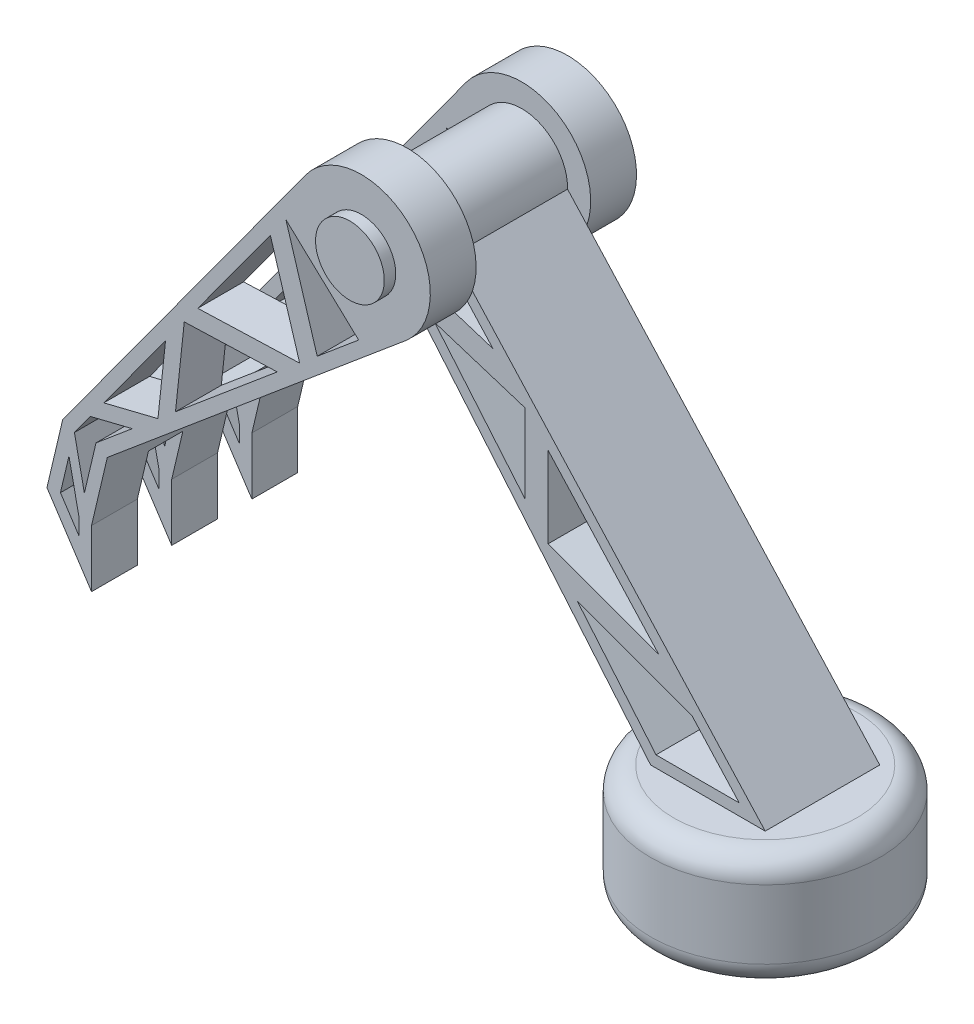
SolidWorks part; units mm, degrees
ref_plane "Front Plane" through (0, 0, 0) normal (0, 0, 1) x (1, 0, 0)
ref_plane "Top Plane" through (0, 0, 0) normal (0, 1, 0) x (1, 0, 0)
ref_plane "Right Plane" through (0, 0, 0) normal (1, 0, 0) x (0, 0, -1)
sketch "Sketch2" plane through (0, 0, 0) normal (0, 1, 0) x (1, 0, 0)
  circle A0 centre (0, 0) radius 12.7
  dimension "D1" = 25.4
extrude "Boss-Extrude1" add sketch "Sketch2" along normal blind 12.7
sketch "Sketch3" plane through (0, 0, 0) normal (0, 0, 1) x (1, 0, 0)
  line L0 (6.35, 12.7) -> (-28.263, 50.6802)
  line L1 (12.7, 12.7) -> (-12.7, 12.7) construction
  line L2 (-6.35, 12.7) -> (-34.1055, 45.7778)
  line L3 (0, 0) -> (0, 23.1747) construction
  line L4 (-12.7, 0) -> (12.7, 0) construction
  line L5 (-34.1055, 45.7778) -> (-28.263, 50.6802) construction
  line L6 (-6.35, 12.7) -> (6.35, 12.7)
  arc A0 (-28.263, 50.6802) -> (-34.1055, 45.7778) centre (-33.3416, 50.8) ccw
  dimension "D5" = 10.16
  dimension "D1" = 6.35
  dimension "D2" = 6.35
  dimension "D3" = 177.656
  dimension "D4" = 7.6269
  dimension "D6" = 50
  dimension "D8" = 50.8
extrude "Boss-Extrude2" add sketch "Sketch3" along normal mid plane 12.7 contours L0 A0 L2 L6
sketch "Sketch4" plane through (0, 0, 6.35) normal (0, 0, 1) x (1, 0, 0)
  line L6 (-5.7578, 13.97) -> (3.4743, 13.97)
  line L7 (3.4743, 13.97) -> (-29.574, 50.2333)
  line L8 (-33.4666, 46.9921) -> (-5.7578, 13.97)
  line L9 (-5.7578, 13.97) -> (3.4743, 13.97)
  line L10 (3.4743, 13.97) -> (-29.574, 50.2333)
  line L11 (-33.4666, 46.9921) -> (-5.7578, 13.97)
  arc A2 (-29.574, 50.2333) -> (-33.4666, 46.9921) centre (-33.3416, 50.8) ccw
  arc A3 (-29.574, 50.2333) -> (-33.4666, 46.9921) centre (-33.3416, 50.8) ccw
  dimension "D1" = 1.27
extrude "Cut-Extrude1" cut sketch "Sketch4" against normal mid plane 15.24 from surface at -6.35 starting at plane "Front Plane"
sketch "Sketch5" plane through (0, 0, 0) normal (0, 0, 1) x (1, 0, 0)
  line L0 (-33.4666, 46.9921) -> (-23.8227, 43.9225)
  line L1 (3.4743, 13.97) -> (-29.574, 50.2333) construction
  line L2 (-30.2987, 43.2168) -> (-20.2707, 40.0249)
  line L3 (-33.4666, 46.9921) -> (-5.7578, 13.97) construction
  line L4 (-20.2707, 40.0249) -> (-20.2707, 31.2658)
  line L5 (-17.7307, 37.2378) -> (-17.7307, 28.2387)
  line L6 (-17.7307, 28.2387) -> (-5.4588, 23.7721)
  line L7 (-14.4653, 24.3472) -> (-1.7727, 19.7275)
  line L8 (-33.4666, 46.9921) -> (-30.2987, 43.2168)
  line L9 (-23.8227, 43.9225) -> (-20.2707, 40.0249)
  line L10 (-20.2707, 40.0249) -> (-17.7307, 37.2378)
  line L11 (-20.2707, 31.2658) -> (-17.7307, 28.2387)
  line L12 (-20.2707, 40.0249) -> (-17.7307, 37.2378)
  line L13 (-20.2707, 31.2658) -> (-17.7307, 28.2387)
  line L14 (-17.7307, 28.2387) -> (-14.4653, 24.3472)
  line L15 (-5.4588, 23.7721) -> (-1.7727, 19.7275)
  dimension "D1" = 2.6367
  dimension "D2" = 2.54
  dimension "D3" = 2.54
  dimension "D4" = 30
  dimension "D5" = 30
extrude "Boss-Extrude3" add sketch "Sketch5" along normal mid plane 12.7 contours L9 L0 L8 L2 | L4 L11 L5 L10 | L15 L6 L14 L7
sketch "Sketch6" plane through (0, 0, 0) normal (0, 0, 1) x (1, 0, 0)
  circle A0 centre (-33.3416, 50.8) radius 3.81
extrude "Boss-Extrude4" add sketch "Sketch6" along normal mid plane 25.4 contours A0
sketch "Sketch7" plane through (0, 0, 12.7) normal (0, 0, 1) x (1, 0, 0)
  line L0 (-39.5174, 55.3023) -> (-66.4507, 18.3575)
  line L1 (-28.4289, 44.9453) -> (-61.5067, 17.1897)
  line L2 (-68.2023, 10.9415) -> (-63.2583, 3.4238)
  line L7 (-66.4507, 18.3575) -> (-61.5067, 17.1897)
  line L8 (-66.4507, 18.3575) -> (-68.2023, 10.9415)
  line L9 (-68.2023, 10.9415) -> (-63.2583, 9.7738)
  line L10 (-61.5067, 17.1897) -> (-63.2583, 9.7738)
  line L11 (-63.2583, 3.4238) -> (-63.2583, 9.7738)
  line L13 (-6.35, 12.7) -> (-34.1055, 45.7778) construction
  circle A0 centre (-33.3416, 50.8) radius 7.6427
  point P6 (-68.7133, -4.0538)
  point P7 (-59.1925, -2.9318)
  point P12 (-59.2512, -3.4222)
  point P13 (-69.1205, 11.2195)
  point P14 (0, 0)
  point P15 (-70.9529, 3.5497)
  point P16 (-65.6187, -4.1352)
  point P17 (-65.1301, 8.8135)
  point P18 (-66.4075, 18.2464)
  point P19 (-61.3266, 12.8735)
  point P20 (-68.7435, 5.8654)
  point P21 (-72.4812, 9.3695)
  point P22 (-67.7507, 15.7352)
  point P23 (-63.1954, 11.7055)
  point P24 (0, 0)
  point P25 (-65.2194, 1.1447)
  point P26 (-63.5309, 1.3428)
  point P27 (-63.3678, 3.5039)
  point P28 (-66.044, 5.6079)
  point P29 (-63.0524, 3.2744)
  circle M15 centre (-33.3416, 50.8) radius 3.81
  dimension "D1" = 15.2855
  dimension "D2" = 6.35
  dimension "D3" = 5.08
  dimension "D4" = 166.093
  dimension "D5" = 7.62
  dimension "D6" = 45.72
  dimension "D7" = 43.18
  dimension "D8" = 90
extrude "Boss-Extrude5" add sketch "Sketch7" along normal blind 5.08 from surface at -6.35 contours A0 M15 | A0 L0 L7 L1 | L10 L7 L8 L9 | L2 L11 L9 starting at face at (-4.6304, 18.0037, 6.35)
sketch "Sketch10" plane through (0, 0, 11.43) normal (0, 0, 1) x (1, 0, 0)
  line L0 (-65.1559, 17.7622) -> (-64.0514, 12.4934)
  line L1 (-65.7598, 15.2053) -> (-64.6553, 9.9365)
  line L2 (-55.8953, 23.7219) -> (-61.894, 22.2366)
  line L3 (-58.739, 21.3358) -> (-63.3903, 20.1841)
  line L6 (-41.7083, 49.9256) -> (-33.6438, 42.3932)
  line L7 (-33.3416, 50.8) -> (-37.676, 46.1594) construction
  line L8 (-41.7083, 49.9256) -> (-38.2371, 38.539)
  line L9 (-43.4313, 47.5622) -> (-40.1828, 36.9063)
  line L10 (-40.1828, 36.9063) -> (-51.4805, 36.5209)
  line L11 (-42.6691, 34.82) -> (-52.9768, 34.4684)
  line L12 (-64.6553, 9.9365) -> (-62.7598, 17.962)
  line L13 (-62.7598, 17.962) -> (-29.3269, 46.0155)
  line L14 (-38.3886, 54.4793) -> (-65.1559, 17.7622)
  line L15 (-65.1559, 17.7622) -> (-66.7043, 11.2062)
  line L16 (-66.7043, 11.2062) -> (-64.6553, 8.0905)
  line L17 (-64.6553, 8.0905) -> (-64.6553, 9.9365)
  line L18 (-64.6553, 9.9365) -> (-62.7598, 17.962)
  line L19 (-62.7598, 17.962) -> (-29.3269, 46.0155)
  line L20 (-38.3886, 54.4793) -> (-65.1559, 17.7622)
  line L21 (-65.1559, 17.7622) -> (-66.7043, 11.2062)
  line L22 (-66.7043, 11.2062) -> (-64.6553, 8.0905)
  line L23 (-64.6553, 8.0905) -> (-64.6553, 9.9365)
  line L24 (-52.9768, 34.4684) -> (-53.9496, 25.3546)
  line L25 (-55.0521, 31.6216) -> (-55.8953, 23.7219)
  arc A2 (-29.3269, 46.0155) -> (-38.3886, 54.4793) centre (-33.3416, 50.8) ccw
  arc A3 (-29.3269, 46.0155) -> (-38.3886, 54.4793) centre (-33.3416, 50.8) ccw
  point P6 (-37.676, 46.1594)
  point P27 (-62.7598, 21.0787)
  dimension "D2" = 6.35
  dimension "D3" = 2.54
  dimension "D4" = 2.54
  dimension "D5" = 2.54
  dimension "D6" = 30
  dimension "D7" = 30
  dimension "D8" = 75
  dimension "D9" = 2.5569
  dimension "D10" = 2.54
  dimension "D11" = 110
  dimension "D1" = 1.397
extrude "Cut-Extrude2" cut sketch "Sketch10" against normal through all contours L9 L20 L10 | L11 L24 L19 | L25 L20 L2 | L22 L23 L1 L21 | L3 L20 L0 L18 L19 | L8 L19 L6
mirror "Mirror1" about plane through (0, 0, 0) normal (0, 0, 1) of bodies 107
sketch "Sketch14" plane through (0, 0, 0) normal (0, -1, 0) x (1, 0, 0)
  circle A0 centre (0, 0) radius 7.62
  circle A1 centre (0, 0) radius 12.7 construction
  circle A2 centre (0, 0) radius 12.7
  dimension "D1" = 5.08
extrude "Cut-Extrude3" cut sketch "Sketch14" against normal blind 6.35 contours A0
sketch "Sketch15" plane through (0, 0, -6.35) normal (0, 0, 1) x (1, 0, 0)
  line L3 (-66.4507, 18.3575) -> (-61.5067, 17.1897)
  line L8 (-39.5174, 55.3023) -> (-66.4507, 18.3575)
  line L9 (-66.4507, 18.3575) -> (-68.2023, 10.9415)
  line L10 (-68.2023, 10.9415) -> (-63.2583, 3.4238)
  line L11 (-63.2583, 3.4238) -> (-63.2583, 9.7738)
  line L12 (-63.2583, 9.7738) -> (-61.5067, 17.1897)
  line L13 (-61.5067, 17.1897) -> (-31.3502, 42.4941)
  line L14 (-31.3502, 42.4941) -> (-34.1055, 45.7778)
  line L15 (-28.263, 50.6802) -> (-26.1123, 48.3203)
  line L17 (-66.4507, 18.3575) -> (-68.2023, 10.9415)
  line L18 (-68.2023, 10.9415) -> (-63.2583, 3.4238)
  line L19 (-63.2583, 3.4238) -> (-63.2583, 9.7738)
  line L20 (-63.2583, 9.7738) -> (-61.5067, 17.1897)
  arc A2 (-26.1123, 48.3203) -> (-39.5174, 55.3023) centre (-33.3416, 50.8) ccw
  arc A3 (-28.263, 50.6802) -> (-34.1055, 45.7778) centre (-33.3416, 50.8) ccw
  line M17 (-66.7043, 11.2062) -> (-65.7598, 15.2053)
  line M18 (-65.7598, 15.2053) -> (-64.6553, 9.9365)
  line M19 (-64.6553, 9.9365) -> (-64.6553, 8.0905)
  line M20 (-64.6553, 8.0905) -> (-66.7043, 11.2062)
  line M22 (-62.7598, 17.962) -> (-64.0514, 12.4934)
  line M23 (-64.0514, 12.4934) -> (-65.1559, 17.7622)
  line M24 (-65.1559, 17.7622) -> (-63.3903, 20.1841)
  line M31 (-66.4507, 18.3575) -> (-68.2023, 10.9415)
  line M32 (-68.2023, 10.9415) -> (-63.2583, 3.4238)
  line M33 (-63.2583, 3.4238) -> (-63.2583, 9.7738)
  line M34 (-63.2583, 9.7738) -> (-61.5067, 17.1897)
  dimension "D1" = 0
extrude "Boss-Extrude12" add sketch "Sketch15" along normal up to next contours L3 M31 M32 M33 M34 M22 M23 M24 M20 M17 M18 M19
fillet "Fillet1" radius 2.54 2 edges at (0, 0, 12.7) (0, 12.7, 12.7)
sketch "Sketch16" plane through (-42.5878, -28.0075, 0) normal (-0.8355, -0.5495, 0) x (0, 0, 1)
  line L0 (11.43, 46.6168) -> (-11.43, 46.6168) construction
  line L1 (-6.35, 46.6168) -> (6.35, 46.6168)
  line L2 (-6.35, 46.6168) -> (-6.35, 37.6191)
  line L3 (-6.35, 37.6191) -> (6.35, 37.6191)
  line L4 (6.35, 46.6168) -> (6.35, 37.6191)
  line L5 (11.43, 37.6191) -> (-11.43, 37.6191) construction
  line L6 (-11.43, 46.6168) -> (-11.43, 37.6191) construction
  line L7 (11.43, 46.6168) -> (11.43, 37.6191) construction
  line L9 (0, 46.6168) -> (0, 37.6191) construction
  line L10 (-2.54, 46.6168) -> (2.54, 46.6168)
  line L11 (-2.54, 46.6168) -> (-2.54, 37.6191)
  line L12 (-2.54, 37.6191) -> (2.54, 37.6191)
  line L13 (2.54, 46.6168) -> (2.54, 37.6191)
  point P19 (3.3521, 45.644)
  point P20 (0, 46.6168)
  point P21 (0, 46.6168)
  point P22 (2.54, 46.6168)
  line M10 (11.43, 46.6168) -> (-11.43, 46.6168)
  line M12 (-11.43, 37.6191) -> (11.43, 37.6191)
  dimension "D1" = 5.08
  dimension "D2" = 5.08
  dimension "D3" = 5.08
extrude "Cut-Extrude5" cut sketch "Sketch16" against normal up to next contours L11 L2 M10 M12 | L13 L4 M10 M12
